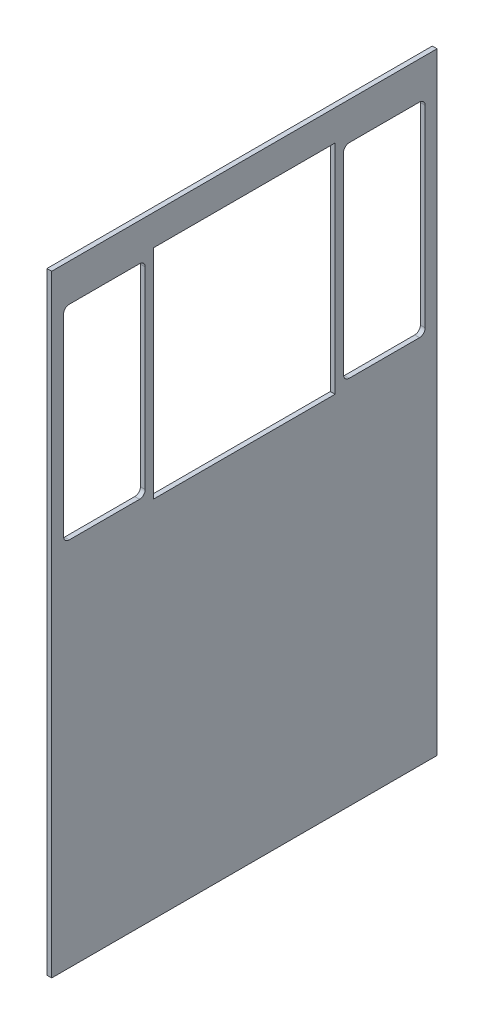
SolidWorks part; units mm, degrees
material "ASTM A36 Steel"
ref_plane "Front Plane" through (0, 0, 0) normal (0, 0, 1) x (1, 0, 0)
ref_plane "Top Plane" through (0, 0, 0) normal (0, 1, 0) x (1, 0, 0)
ref_plane "Right Plane" through (0, 0, 0) normal (1, 0, 0) x (0, 0, -1)
sketch "Sketch1" plane through (0, 0, 0) normal (1, 0, 0) x (0, 0, -1)
  line L0 (0, 0) -> (0, 349.25) construction
  line L1 (98.1075, 207.645) -> (58.7375, 207.645)
  line L2 (114.3, 0) -> (-114.3, 0)
  line L3 (114.3, 0) -> (114.3, 349.25)
  line L4 (114.3, 349.25) -> (-114.3, 349.25)
  line L5 (-114.3, 0) -> (-114.3, 349.25)
  line L6 (114.3, 0) -> (-114.3, 349.25) construction
  line L7 (114.3, 349.25) -> (-114.3, 0) construction
  line L8 (50.8, 203.835) -> (-50.8, 203.835)
  line L9 (50.8, 203.835) -> (50.8, 325.755)
  line L10 (50.8, 325.755) -> (-50.8, 325.755)
  line L11 (-50.8, 203.835) -> (-50.8, 325.755)
  line L12 (50.8, 203.835) -> (-50.8, 325.755) construction
  line L13 (50.8, 325.755) -> (-50.8, 203.835) construction
  line L14 (-98.1075, 207.645) -> (-58.7375, 207.645)
  line L15 (-101.2825, 210.82) -> (-101.2825, 318.77)
  line L16 (-98.1075, 321.945) -> (-58.7375, 321.945)
  line L17 (-55.5625, 210.82) -> (-55.5625, 318.77)
  line L18 (98.1075, 321.945) -> (58.7375, 321.945)
  line L19 (55.5625, 210.82) -> (55.5625, 318.77)
  line L20 (101.2825, 210.82) -> (101.2825, 318.77)
  arc A6 (-55.5625, 210.82) -> (-58.7375, 207.645) centre (-58.7375, 210.82) cw
  arc A7 (-101.2825, 210.82) -> (-98.1075, 207.645) centre (-98.1075, 210.82) ccw
  arc A8 (-98.1075, 321.945) -> (-101.2825, 318.77) centre (-98.1075, 318.77) ccw
  arc A9 (-58.7375, 321.945) -> (-55.5625, 318.77) centre (-58.7375, 318.77) cw
  arc A10 (98.1075, 321.945) -> (101.2825, 318.77) centre (98.1075, 318.77) cw
  arc A11 (58.7375, 321.945) -> (55.5625, 318.77) centre (58.7375, 318.77) ccw
  arc A12 (55.5625, 210.82) -> (58.7375, 207.645) centre (58.7375, 210.82) ccw
  arc A13 (101.2825, 210.82) -> (98.1075, 207.645) centre (98.1075, 210.82) cw
  point P3 (0, 174.625)
  point P14 (0, 264.795)
  point P39 (-101.2825, 207.645)
  point P42 (-101.2825, 321.945)
  dimension "D5" = 121.92
  dimension "D12" = 3.175
  dimension "D8" = 114.3
  dimension "D1" = 349.25
  dimension "D2" = 228.6
  dimension "D4" = 101.6
  dimension "D6" = 23.495
  dimension "D9" = 45.72
  dimension "D10" = 27.305
  dimension "D11" = 55.5625
extrude "Boss-Extrude1" add sketch "Sketch1" along normal blind 2.667
sketch "Sketch2" plane through (2.667, 0, 0) normal (1, 0, 0) x (0, 0, -1)
  line L0 (-114.3, 349.25) -> (-114.3, 0) construction
  line L1 (114.3, 349.25) -> (-114.3, 349.25) construction
  line L2 (114.3, 0) -> (114.3, 349.25) construction
  line L3 (-114.3, 349.25) -> (-114.3, 0)
  line L4 (114.3, 349.25) -> (-114.3, 349.25)
  line L5 (114.3, 0) -> (114.3, 349.25)
  line L6 (107.95, 0) -> (107.95, 342.9)
  line L7 (107.95, 342.9) -> (-107.95, 342.9)
  line L8 (-107.95, 342.9) -> (-107.95, 0)
  line M9 (-114.3, 349.25) -> (-114.3, 0)
  line M10 (-114.3, 0) -> (114.3, 0)
  line M11 (114.3, 0) -> (114.3, 349.25)
  line M12 (114.3, 349.25) -> (-114.3, 349.25)
  dimension "D1" = 6.35
extrude "CornerRadiusAllowance" cut sketch "Sketch2" against normal through all contours L8 L7 L6 M10 M11 M12 M9
